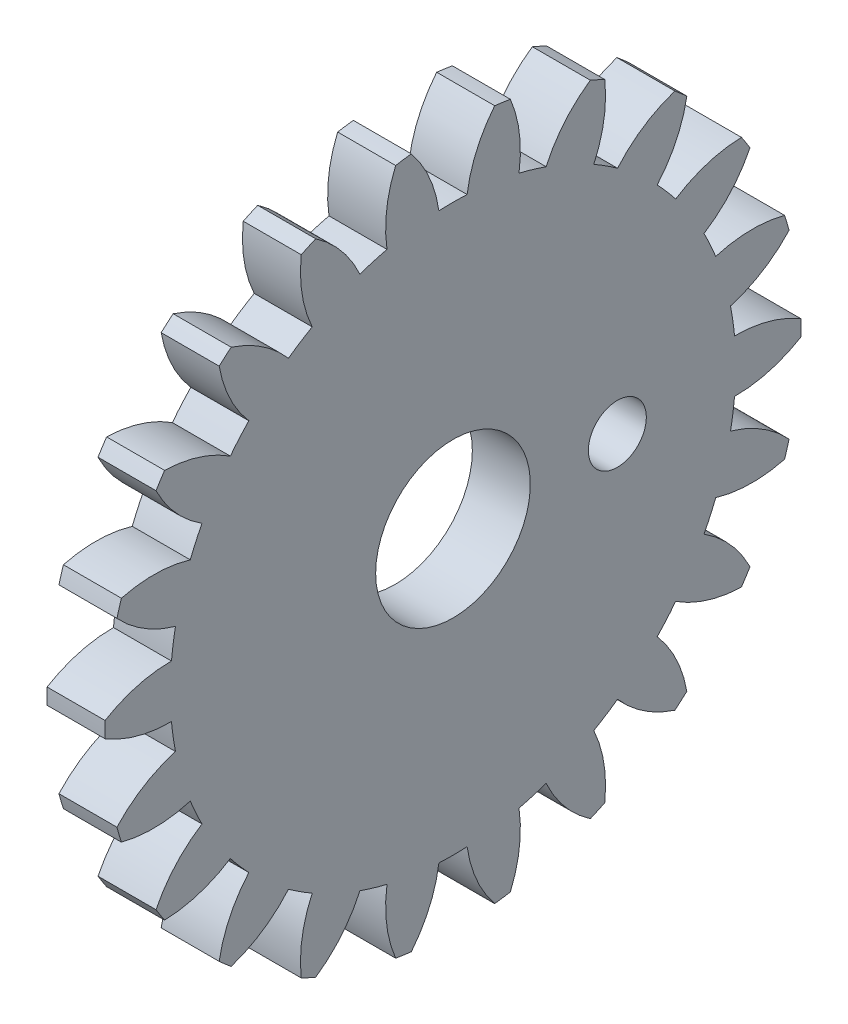
SolidWorks part; units mm, degrees
ref_plane "Plane1" through (0, 0, 0) normal (0, 0, 1) x (1, 0, 0)
ref_plane "Plane2" through (0, 0, 0) normal (0, 1, 0) x (1, 0, 0)
ref_plane "Plane3" through (0, 0, 0) normal (1, 0, 0) x (0, 0, -1)
sketch "HoldingSke" plane through (0, 0, 0) normal (0, 1, 0) x (1, 0, 0)
  line L0 (0, 0) -> (0.6181, -0.2497)
  line L1 (-15, 0) -> (100, 0) construction
  line L2 (0, 0) -> (-2.1039, 2.3779)
  line L3 (0, 0) -> (-11.863, 4.5341)
  line L4 (0, 0) -> (8.0072, 3.2351)
  line L5 (0, 0) -> (-46.8476, -17.4728)
  line L6 (0, 0) -> (-2.4869, -1.6779)
  line L7 (-2.1039, 2.3779) -> (8.6586, 51.2059)
  line L8 (-76.2, 54.61) -> (-75.5, 54.61)
  line L9 (-71.009, 38.7566) -> (-53.1078, 45.2721)
  line L10 (-76.2, 71.12) -> (104.1128, 71.12)
  line L11 (0, 0) -> (-3, 0)
  line L12 (-76.2, 101.6) -> (-76.147, 101.6)
  line L13 (24.9733, 27.94) -> (52.9518, 28.4284)
  line L14 (24.9733, 27.94) -> (24.9743, 27.94)
  line L15 (24.9733, 27.94) -> (100.4006, 29.5858)
  line L16 (-63.627, -1.5) -> (-12.827, -1.5)
  circle A0 centre (0, 0) radius 2
  circle A1 centre (0, 0) radius 14.624
  circle A2 centre (0, 0) radius 37.5
  circle A3 centre (0, 0) radius 2
  dimension "MHD" = 29.248
  dimension "Hub_dia" = 75
  dimension "Bore" = 4
  dimension "MBD" = 4
  dimension "Num_teeth" = 22
  dimension "Pitch" = 0.6667
  dimension "Overall_len" = 50
  dimension "Show_teeth" = 22
  dimension "Thickness" = 3
  dimension "OAL" = 50.0001
  dimension "T_dim" = 0.7
  dimension "Ap" = 20
  dimension "H" = 19.05
  dimension "Pitch_radius" = 180.3128
  dimension "Width" = 3
  dimension "Backlash" = 0.053
  dimension "Addendum_fac" = 1
  dimension "Dedendum_fac" = 1.25
  dimension "Clearance_fac" = 0.25
  dimension "Dedendum_add" = 0.001
  dimension "Module" = 1.5
sketch "BasProSke" plane through (0, 0, 0) normal (0, 1, 0) x (1, 0, 0)
  line L0 (-10, 0) -> (60, 0) construction
  line L1 (0, 0) -> (0, 18)
  line L2 (0, 0) -> (3, 0)
  line L3 (3, 0) -> (3, 18)
  line L4 (3, 18) -> (0, 18)
  dimension "Thickness" = 3
  dimension "Diameter" = 36
revolve "Base-Revolve" add sketch "BasProSke" angle 360 about L0
sketch "TooCutSke" plane through (0, 0, 0) normal (1, 0, 0) x (0, 0, -1)
  line L1 (0, 0) -> (0, 107) construction
  line L2 (0, 0) -> (-1.2698, 16.4511) construction
  line L3 (0, 0) -> (-4.6862, 32.5935) construction
  line L4 (-1.2698, 16.4511) -> (-2.3431, 16.2967) construction
  arc A0 (0.7304, 14.6058) -> (-0.7304, 14.6058) centre (0, 0) ccw
  arc A1 (2.1742, 17.8938) -> (-2.1742, 17.8938) centre (0, 0) ccw
  circle A2 centre (0, 0) radius 16.5 construction
  circle A3 centre (0, 0) radius 15.5049 construction
  arc A4 (-0.7304, 14.6058) -> (-2.1742, 17.8938) centre (-7.2674, 13.6963) ccw
  arc A5 (2.1742, 17.8938) -> (0.7304, 14.6058) centre (7.2674, 13.6963) ccw
  dimension "Root_dia" = 29.248
  dimension "Overcut_dia" = 36.0508
  dimension "Pitch_dia" = 33
  dimension "Base_dia" = 31.0099
  dimension "Flank_rad" = 6.6
  dimension "Half_ang" = 8.182
  dimension "Half_CT" = 1.0843
extrude "ToothCut" cut sketch "TooCutSke" along normal through all
fillet "Breaks" [suppressed] radius 0.03
fillet "RootFillets" [suppressed] radius 0.376
pattern_circular "TeethCuts" count 22 every 16.364 about axis through (-10, 0, 0) along (1, 0, 0) of "ToothCut", "RootFillets", "Breaks"
sketch "HubNeaOneSke" plane through (0, 0, 0) normal (-1, 0, 0) x (0, 0, 1)
  circle A0 centre (0, 0) radius 14.624
  dimension "Diameter" = 29.248
extrude "HubNearOne" [suppressed] add sketch "HubNeaOneSke" along normal blind 47.0001
sketch "HubNeaBotSke" plane through (0, 0, 0) normal (-1, 0, 0) x (0, 0, 1)
  circle A0 centre (0, 0) radius 14.624
  dimension "Diameter" = 29.248
extrude "HubNearBoth" [suppressed] add sketch "HubNeaBotSke" along normal blind 23.5
ref_plane "FarPln" through (3, 0, 0) normal (1, 0, 0) x (0, 0, -1)
sketch "HubFarSke" plane through (3, 0, 0) normal (1, 0, 0) x (0, 0, -1)
  circle A0 centre (0, 0) radius 14.624
  dimension "Diameter" = 29.248
extrude "HubFar" [suppressed] add sketch "HubFarSke" along normal blind 23.5
sketch "BorSke" plane through (0, 0, 0) normal (1, 0, 0) x (0, 0, -1)
  circle A0 centre (0, 0) radius 4
  dimension "Diameter" = 8
extrude "Bore" cut sketch "BorSke" along normal mid plane 100.0001
sketch "KeySke" plane through (0, 0, 0) normal (1, 0, 0) x (0, 0, -1)
  line L0 (-0.8, 0) -> (-0.8, 2.7)
  line L1 (-0.8, 2.7) -> (0.8, 2.7)
  line L2 (0.8, 2.7) -> (0.8, 0)
  line L3 (0, 0) -> (0, 34) construction
  line L4 (-0.8, 0) -> (0.8, 0)
  dimension "Offset" = 2.7
  dimension "Width" = 1.6
extrude "Keyway" [suppressed] cut sketch "KeySke" along normal mid plane 100.0001
pattern_circular "Keyway2" [suppressed] count 2 every 90 about axis through (-10, 0, 0) along (1, 0, 0)
sketch "草图1" plane through (3, 0, 0) normal (1, 0, 0) x (0, 0, -1)
  line L0 (0, 0) -> (8.5, 0) construction
  circle A0 centre (8.5, 0) radius 1.5
  dimension "D1" = 3
  dimension "D2" = 8.5
extrude "切除-拉伸1" cut sketch "草图1" against normal through all
equation "' \"Module@HoldingSke\" = 6.35"
equation "' \"Num_teeth@HoldingSke\" = 12"
equation "' \"Ap@HoldingSke\" =  20"
equation "' \"Ap@HoldingSke\" = 20"
equation "' \"Width@HoldingSke\" = 0.5 * 25.4"
equation "' \"Hub_dia@HoldingSke\"= 1 * 25.4"
equation "' \"Hub_dia@HoldingSke\" = 1 * 25.4"
equation "' \"Overall_len@HoldingSke\" = 1.0 * 25.4"
equation "' \"Bore@HoldingSke\" = 0.75 * 25.4"
equation "' \"T_dim@HoldingSke\" = 0.1 * 25.4"
equation "' \"Width@KeySke\" = 0.25 * 25.4"
equation "' \"Show_teeth@HoldingSke\" = 13"
equation "' \"Backlash@HoldingSke\" = 0.009 * 25.4"
equation "' \"Addendum_fac@HoldingSke\" = 1.0"
equation "' \"Dedendum_fac@HoldingSke\" = 1.25"
equation "' \"Dedendum_add@HoldingSke\" = 0.00005 * 25.4"
equation "' \"Clearance_fac@HoldingSke\" = 0.25"
equation "\"Pitch@HoldingSke\" = 1 / \"Module@HoldingSke\""
equation "\"Overcut_dia@TooCutSke\" = (\"Num_teeth@HoldingSke\" + 2 * \"Addendum_fac@HoldingSke\") / \"Pitch@HoldingSke\" + 0.002 * 25.4"
equation "\"Pitch_dia@TooCutSke\" = \"Num_teeth@HoldingSke\" / \"Pitch@HoldingSke\""
equation "\"Base_dia@TooCutSke\" = \"Num_teeth@HoldingSke\" / \"Pitch@HoldingSke\" * cos((\"Ap@HoldingSke\"  * 3.14159265 / 180))"
equation "\"Root_dia@TooCutSke\" = (\"Num_teeth@HoldingSke\" + 2) / \"Pitch@HoldingSke\" - 2 * (\"Addendum_fac@HoldingSke\" + \"Dedendum_fac@HoldingSke\") / \"Pitch@HoldingSke\" - \"Dedendum_add@HoldingSke\" * 2"
equation "\"Half_ang@TooCutSke\" = 180 / \"Num_teeth@HoldingSke\""
equation "\"Half_CT@TooCutSke\" = \"Num_teeth@HoldingSke\" / \"Pitch@HoldingSke\" * sin((3.14159265 / 2 / \"Num_teeth@HoldingSke\")) / 2 - 7 * \"Backlash@HoldingSke\" / 4"
equation "\"Flank_rad@TooCutSke\" = \"Num_teeth@HoldingSke\" / \"Pitch@HoldingSke\" / 5"
equation "\"Radius@RootFillets\" = \"Clearance_fac@HoldingSke\" / \"Pitch@HoldingSke\" + \"Dedendum_add@HoldingSke\""
equation "\"Break_rad@Breaks\" = 0.02 / \"Pitch@HoldingSke\""
equation "\"Thickness@HoldingSke\" = \"Width@HoldingSke\""
equation "\"OAL@HoldingSke\" = \"Thickness@HoldingSke\""
equation "\"MHD@HoldingSke\" = (\"Num_teeth@HoldingSke\" + 2) / \"Pitch@HoldingSke\" - 2 * (\"Addendum_fac@HoldingSke\" + \"Dedendum_fac@HoldingSke\")  / \"Pitch@HoldingSke\" - \"Dedendum_add@HoldingSke\" * 2"
equation "\"MBD@HoldingSke\" = (\"Num_teeth@HoldingSke\" + 2) / \"Pitch@HoldingSke\" - 2 * (\"Addendum_fac@HoldingSke\" + \"Dedendum_fac@HoldingSke\")  / \"Pitch@HoldingSke\" - \"Dedendum_add@HoldingSke\" * 2 - 0.002 * 25.4"
equation "\"MHD@HoldingSke\" = ((sgn( \"MHD@HoldingSke\" - \"Hub_dia@HoldingSke\" )-1)*( \"MHD@HoldingSke\" - \"Hub_dia@HoldingSke\" ))/-2+ \"Hub_dia@HoldingSke\""
equation "\"MBD@HoldingSke\" = ((sgn( \"MBD@HoldingSke\" - \"Bore@HoldingSke\" )-1)*( \"MBD@HoldingSke\" - \"Bore@HoldingSke\" ))/-2+ \"Bore@HoldingSke\""
equation "\"OAL@HoldingSke\" = ((sgn( \"OAL@HoldingSke\" - \"Overall_len@HoldingSke\" )+1)*( \"OAL@HoldingSke\" - \"Overall_len@HoldingSke\" ))/2 + \"Overall_len@HoldingSke\" + 0.000002 * 25.4"
equation "\"Num_teeth@TeethCuts\" = int( \"Show_teeth@HoldingSke\" ) + 1"
equation "\"Num_teeth@TeethCuts\" = ((sgn( \"Num_teeth@TeethCuts\" - \"Num_teeth@HoldingSke\" )-1)*( \"Num_teeth@TeethCuts\" - \"Num_teeth@HoldingSke\" ))/-2+ \"Num_teeth@HoldingSke\""
equation "\"Num_teeth@TeethCuts\" = ((sgn( \"Num_teeth@TeethCuts\" - 2.0)+1)*( \"Num_teeth@TeethCuts\" - 2.0))/2 +2.0"
equation "\"Angle@TeethCuts\" = 360.0 / \"Num_teeth@HoldingSke\""
equation "\"Diameter@BasProSke\" = (\"Num_teeth@HoldingSke\" + 2 * \"Addendum_fac@HoldingSke\") / \"Pitch@HoldingSke\""
equation "\"Thickness@BasProSke\"  = \"Thickness@HoldingSke\""
equation "' \"Fillet_rad@BasProSke\" =  \"Thickness@HoldingSke\" * 0.05"
equation "' \"Fillet_rad@BasProSke\" = \"Thickness@HoldingSke\" * 0.05"
equation "\"MHD@HoldingSke\" = ((sgn( \"MHD@HoldingSke\" - \"Root_dia@TooCutSke\" )-1)*( \"MHD@HoldingSke\" - \"Root_dia@TooCutSke\" ))/-2+ \"Root_dia@TooCutSke\""
equation "\"Diameter@HubNeaOneSke\" = \"MHD@HoldingSke\""
equation "\"Length@HubNearOne\" = \"OAL@HoldingSke\" - \"Thickness@BasProSke\""
equation "\"Diameter@HubNeaBotSke\" = \"MHD@HoldingSke\""
equation "\"Length@HubNearBoth\" = ( \"OAL@HoldingSke\" - \"Thickness@BasProSke\" ) / 2.0"
equation "\"Thickness@FarPln\" = \"Thickness@BasProSke\""
equation "\"Diameter@HubFarSke\" = \"MHD@HoldingSke\""
equation "\"Length@HubFar\" = ( \"OAL@HoldingSke\" - \"Thickness@BasProSke\" ) / 2.0"
equation "\"D1@Bore\" = \"OAL@HoldingSke\" * 2.0"
equation "\"D1@Keyway\" = \"OAL@HoldingSke\" * 2.0"
equation "\"Offset@KeySke\" = \"T_dim@HoldingSke\" + \"MBD@HoldingSke\" / 2.0"
